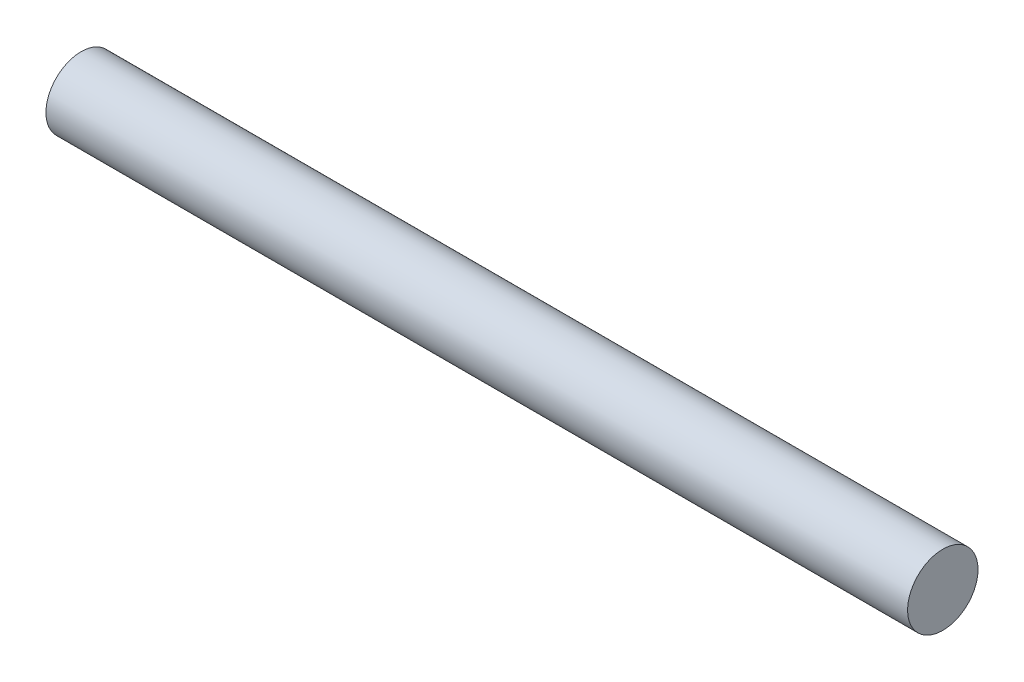
SolidWorks part; units mm, degrees
ref_plane "Front Plane" through (0, 0, 0) normal (0, 0, 1) x (1, 0, 0)
ref_plane "Top Plane" through (0, 0, 0) normal (0, 1, 0) x (1, 0, 0)
ref_plane "Right Plane" through (0, 0, 0) normal (1, 0, 0) x (0, 0, -1)
sketch "Sketch1" plane through (0, 0, 0) normal (1, 0, 0) x (0, 0, -1)
  circle A0 centre (0, 0) radius 2.45
extrude "Boss-Extrude1" add sketch "Sketch1" along normal blind 60
